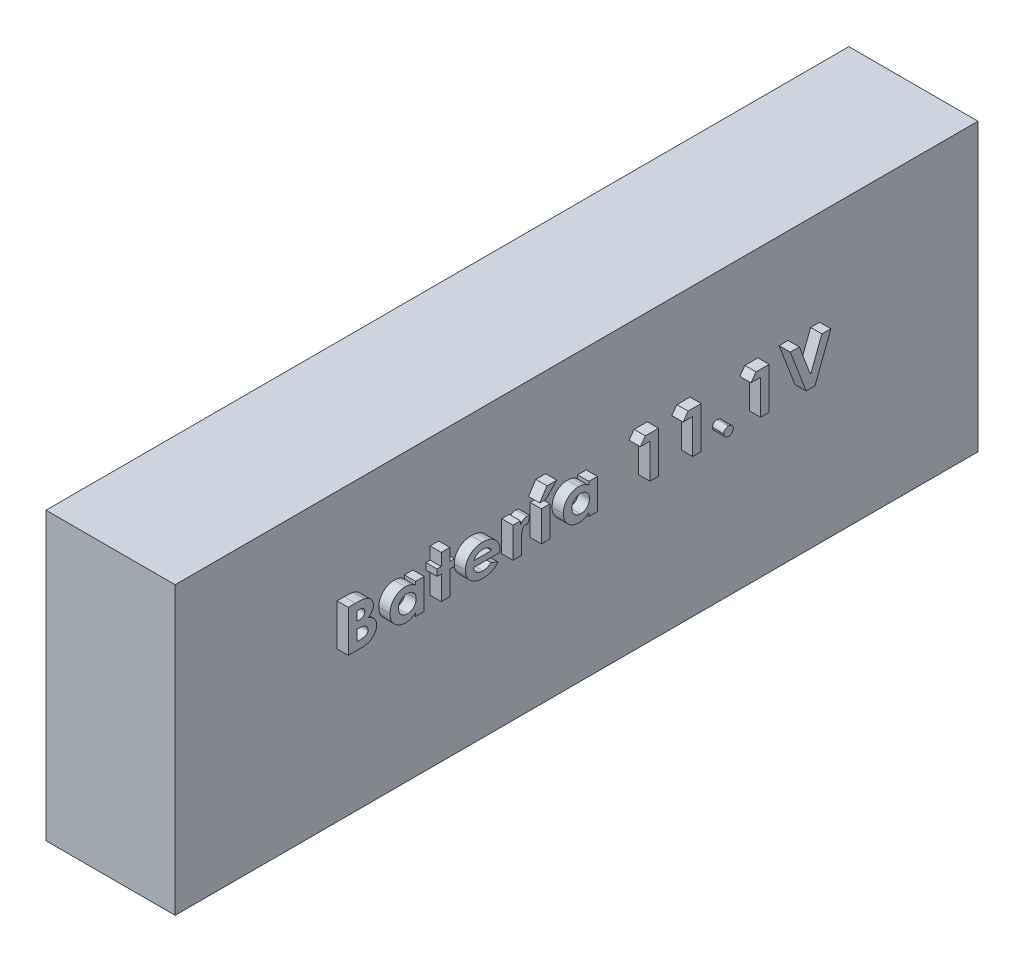
SolidWorks part; units mm, degrees
ref_plane "Alzado" through (0, 0, 0) normal (0, 0, 1) x (1, 0, 0)
ref_plane "Planta" through (0, 0, 0) normal (0, 1, 0) x (1, 0, 0)
ref_plane "Vista lateral" through (0, 0, 0) normal (1, 0, 0) x (0, 0, -1)
sketch "Croquis1" plane through (0, 0, 0) normal (0, 0, 1) x (1, 0, 0)
  line L1 (0, 0) -> (23, 0)
  line L2 (0, 0) -> (0, 51)
  line L3 (0, 51) -> (23, 51)
  line L4 (23, 0) -> (23, 51)
  dimension "D1" = 23
  dimension "D2" = 51
extrude "Saliente-Extruir1" add sketch "Croquis1" along normal blind 143
sketch "Croquis3" plane through (23, 0, 0) normal (1, 0, 0) x (0, 0, -1)
  text T0 "<b>Batería 11.1V</b>" font "Century Gothic" height in points 28
extrude "Saliente-Extruir4" add sketch "Croquis3" along normal blind 2
